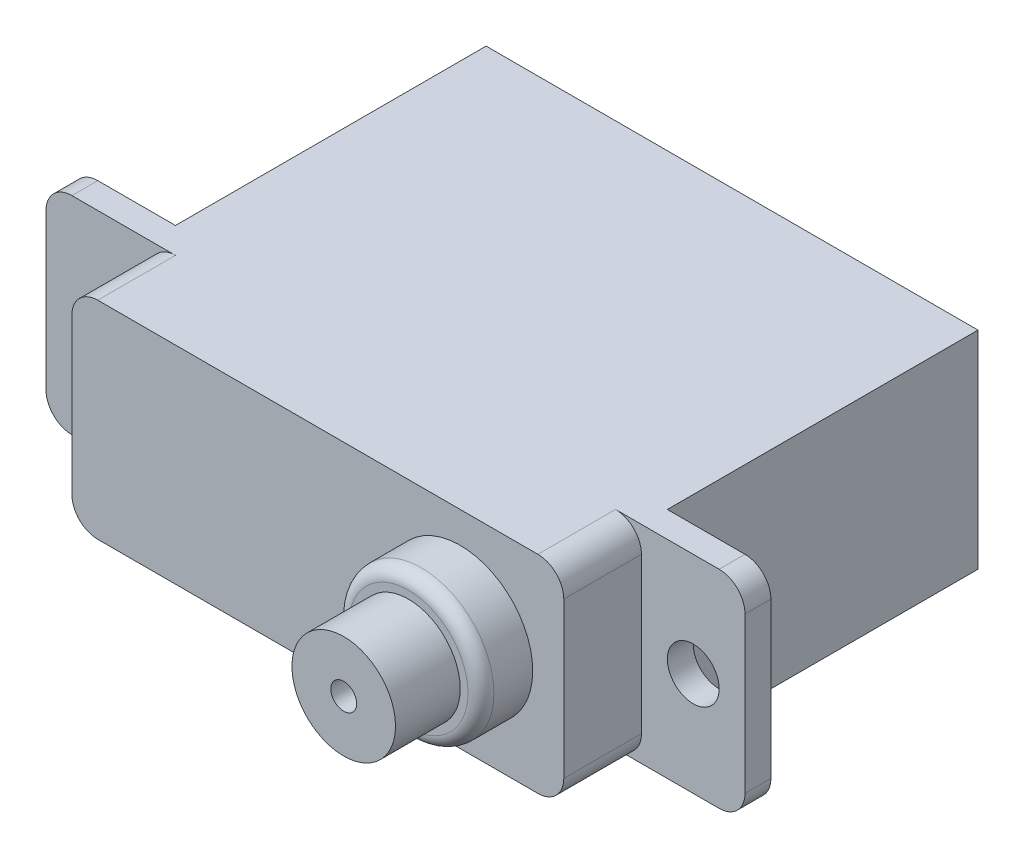
SolidWorks part; units mm, degrees
ref_plane "Ön Düzlem" through (0, 0, 0) normal (0, 0, 1) x (1, 0, 0)
ref_plane "Üst Düzlem" through (0, 0, 0) normal (0, 1, 0) x (1, 0, 0)
ref_plane "Sağ Düzlem" through (0, 0, 0) normal (1, 0, 0) x (0, 0, -1)
sketch "Çizim1" plane through (0, 0, 0) normal (0, 0, 1) x (1, 0, 0)
  line L1 (-9.5, -4) -> (9.5, -4)
  line L2 (-9.5, -4) -> (-9.5, 4)
  line L3 (-9.5, 4) -> (9.5, 4)
  line L4 (9.5, -4) -> (9.5, 4)
  line L5 (-9.5, -4) -> (9.5, 4) construction
  line L6 (-9.5, 4) -> (9.5, -4) construction
  point P0 (0, 0)
extrude "Yükseklik-Ekstrüzyon1" add sketch "Çizim1" along normal blind 12
sketch "Çizim2" plane through (0, 0, 12) normal (0, 0, 1) x (1, 0, 0)
  line L1 (-12.5, -4) -> (12.5, -4)
  line L2 (-13.5, -3) -> (-13.5, 3)
  line L3 (-12.5, 4) -> (12.5, 4)
  line L4 (13.5, -3) -> (13.5, 3)
  circle A0 centre (-11.5, 0) radius 1
  circle A1 centre (11.5, 0) radius 1
  arc A2 (12.5, 4) -> (13.5, 3) centre (12.5, 3) cw
  arc A3 (12.5, -4) -> (13.5, -3) centre (12.5, -3) ccw
  arc A4 (-12.5, -4) -> (-13.5, -3) centre (-12.5, -3) cw
  arc A5 (-13.5, 3) -> (-12.5, 4) centre (-12.5, 3) cw
  point P0 (0, 0)
extrude "Yükseklik-Ekstrüzyon2" add sketch "Çizim2" along normal blind 1
sketch "Çizim3" plane through (0, 0, 13) normal (0, 0, 1) x (1, 0, 0)
  line L0 (12.5, 4) -> (-12.5, 4) construction
  line L1 (-8.5, -4) -> (8.5, -4)
  line L2 (-9.5, -3) -> (-9.5, 3)
  line L3 (-8.5, 4) -> (8.5, 4)
  line L4 (9.5, -3) -> (9.5, 3)
  arc A0 (8.5, -4) -> (9.5, -3) centre (8.5, -3) ccw
  arc A1 (8.5, 4) -> (9.5, 3) centre (8.5, 3) cw
  arc A2 (-8.5, -4) -> (-9.5, -3) centre (-8.5, -3) cw
  arc A3 (-9.5, 3) -> (-8.5, 4) centre (-8.5, 3) cw
  point P0 (0, 0)
  point P12 (9.5, 4)
  dimension "D1" = 1
extrude "Yükseklik-Ekstrüzyon3" add sketch "Çizim3" along normal blind 3
sketch "Çizim4" plane through (0, 0, 16) normal (0, 0, 1) x (1, 0, 0)
  line L0 (9.5, 0) -> (5.5, 0) construction
  line L1 (9.5, -3) -> (9.5, 3) construction
  circle A0 centre (5.5, 0) radius 2.8
extrude "Yükseklik-Ekstrüzyon4" add sketch "Çizim4" along normal blind 2
sketch "Çizim5" plane through (0, 0, 18) normal (0, 0, 1) x (1, 0, 0)
  circle A0 centre (5.5, 0) radius 2
extrude "Yükseklik-Ekstrüzyon5" add sketch "Çizim5" along normal blind 2.5
sketch "Çizim6" plane through (0, 0, 20.5) normal (0, 0, 1) x (1, 0, 0)
  circle A0 centre (5.5, 0) radius 0.5
extrude "Kes-Ekstrüzyon1" cut sketch "Çizim6" against normal blind 5
fillet "Radyus1" radius 0.5 1 edges at (8.3, 0, 18)
